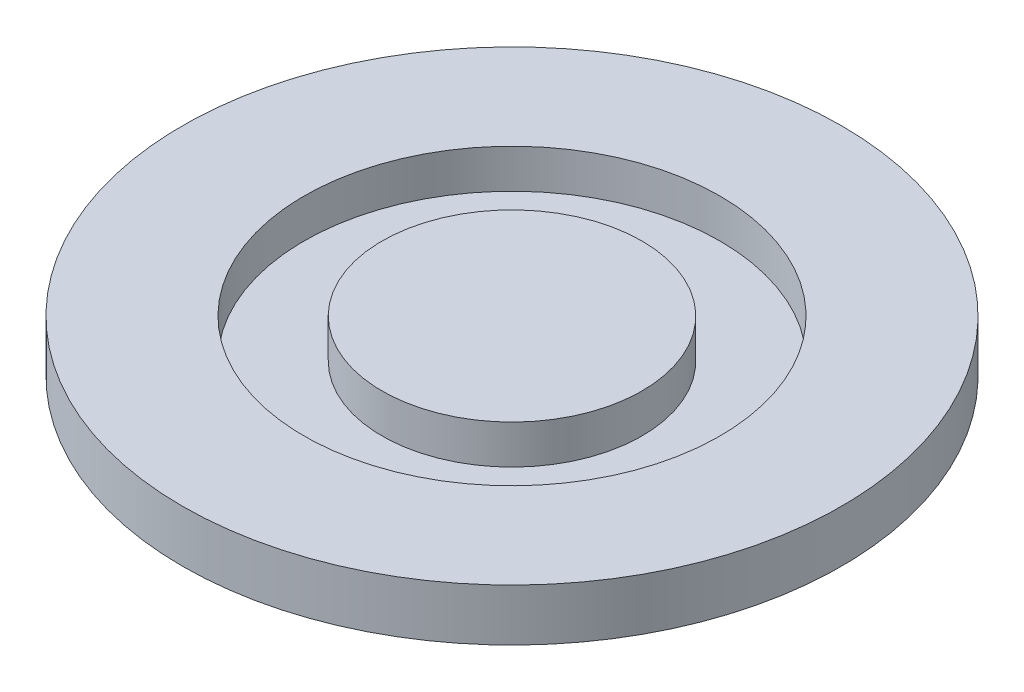
SolidWorks part; units mm, degrees
ref_plane "Front Plane" through (0, 0, 0) normal (0, 0, 1) x (1, 0, 0)
ref_plane "Top Plane" through (0, 0, 0) normal (0, 1, 0) x (1, 0, 0)
ref_plane "Right Plane" through (0, 0, 0) normal (1, 0, 0) x (0, 0, -1)
sketch "Sketch1" plane through (0, 0, 0) normal (0, 0, 1) x (1, 0, 0)
  line L0 (0, 0) -> (0, 12.7)
  line L14 (0, 12.7) -> (31.75, 12.7)
  line L18 (50.8, 12.7) -> (80.512, 12.7)
  line L19 (80.512, 12.7) -> (80.512, 0)
  line L20 (80.512, 0) -> (0, 0)
  line L21 (0, 0) -> (0, 67.1864) construction
  line L22 (31.75, 12.7) -> (31.75, 3.175)
  line L23 (31.75, 3.175) -> (50.8, 3.175)
  line L24 (50.8, 3.175) -> (50.8, 12.7)
  dimension "D1" = 161.024
  dimension "D2" = 3.175
  dimension "D3" = 63.5
  dimension "D4" = 101.6
  dimension "D5" = 9.525
  dimension "D6" = 12.7
revolve "Revolve1" add sketch "Sketch1" angle 360 about L21
